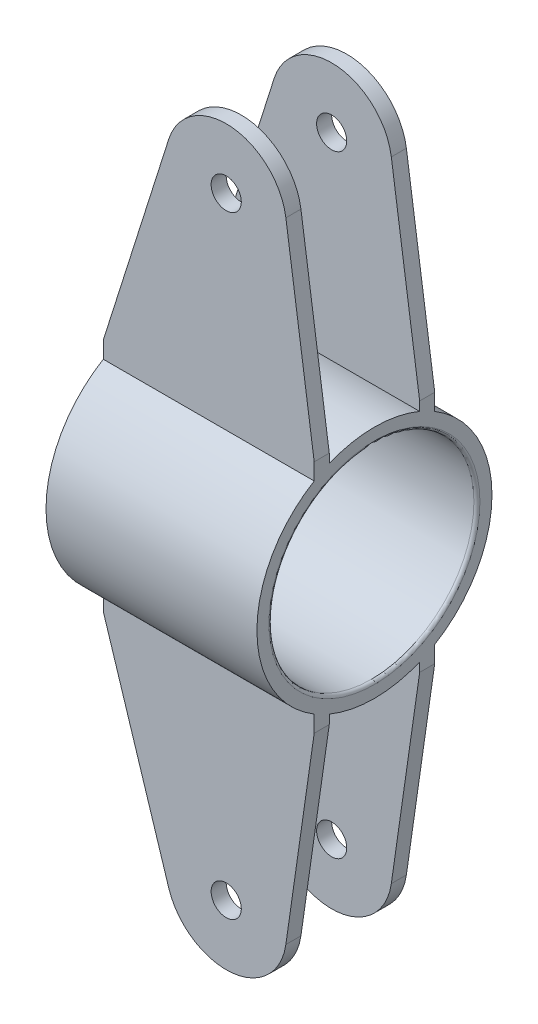
SolidWorks part; units mm, degrees
ref_plane "Front Plane" through (0, 0, 0) normal (0, 0, 1) x (1, 0, 0)
ref_plane "Top Plane" through (0, 0, 0) normal (0, 1, 0) x (1, 0, 0)
ref_plane "Right Plane" through (0, 0, 0) normal (1, 0, 0) x (0, 0, -1)
sketch "Sketch1" plane through (0, 0, 0) normal (1, 0, 0) x (0, 0, -1)
  circle A0 centre (0, 0) radius 34.007
  circle A1 centre (0, 0) radius 39.007
  dimension "D1" = 68.014
  dimension "D2" = 78.014
extrude "Boss-Extrude1" add sketch "Sketch1" along normal mid plane 70
sketch "Sketch2" plane through (0, 0, 0) normal (0, 0, 1) x (1, 0, 0)
  line L0 (-35, 0) -> (5.8, 0) construction
  line L1 (-35, 39.007) -> (-35, -39.007) construction
  line L2 (5.8, 101.6) -> (5.8, -101.6) construction
  line L3 (-35, -39.007) -> (35, -39.007) construction
  line L4 (35, 39.007) -> (-35, 39.007) construction
  line L5 (-35, -39.007) -> (35, -39.007)
  line L6 (35, 39.007) -> (-35, 39.007)
  line L7 (-35, 39.007) -> (-13.2668, 107.6378)
  line L8 (35, 39.007) -> (25.5966, 104.4448)
  line L9 (-35, -39.007) -> (-13.2668, -107.6378)
  line L10 (35, -39.007) -> (25.5966, -104.4448)
  circle A0 centre (5.8, 101.6) radius 5.007
  circle A1 centre (5.8, -101.6) radius 5.007
  arc A2 (25.5966, 104.4448) -> (-13.2668, 107.6378) centre (5.8, 101.6) ccw
  arc A3 (-13.2668, -107.6378) -> (25.5966, -104.4448) centre (5.8, -101.6) ccw
  point P8 (5.8, 0)
  dimension "D3" = 10.014
  dimension "D4" = 40
  dimension "D1" = 40.8
  dimension "D2" = 203.2
extrude "Boss-Extrude2" add sketch "Sketch2" along normal blind 5 from offset 15 separate body
sketch "Sketch3" plane through (0, 0, 0) normal (0, 0, 1) x (1, 0, 0)
  line L0 (-35, -39.007) -> (-13.2668, -107.6378) construction
  line L1 (25.5966, -104.4448) -> (35, -39.007) construction
  line L2 (35, -39.007) -> (-35, -39.007) construction
  line L3 (-35, 39.007) -> (35, 39.007) construction
  line L4 (-13.2668, 107.6378) -> (-35, 39.007) construction
  line L5 (35, 39.007) -> (25.5966, 104.4448) construction
  line L6 (-35, -39.007) -> (-13.2668, -107.6378)
  line L7 (25.5966, -104.4448) -> (35, -39.007)
  line L8 (35, -39.007) -> (-35, -39.007)
  line L9 (-35, 39.007) -> (35, 39.007)
  line L10 (-13.2668, 107.6378) -> (-35, 39.007)
  line L11 (35, 39.007) -> (25.5966, 104.4448)
  circle A0 centre (5.8, -101.6) radius 5.007 construction
  arc A1 (-13.2668, -107.6378) -> (25.5966, -104.4448) centre (5.8, -101.6) ccw construction
  circle A2 centre (5.8, 101.6) radius 5.007 construction
  arc A3 (25.5966, 104.4448) -> (-13.2668, 107.6378) centre (5.8, 101.6) ccw construction
  circle A4 centre (5.8, -101.6) radius 5.007
  arc A5 (-13.2668, -107.6378) -> (25.5966, -104.4448) centre (5.8, -101.6) ccw
  circle A6 centre (5.8, 101.6) radius 5.007
  arc A7 (25.5966, 104.4448) -> (-13.2668, 107.6378) centre (5.8, 101.6) ccw
extrude "Boss-Extrude3" add sketch "Sketch3" against normal blind 5 from offset 15 separate body offset against normal yes
sketch "Sketch4" plane through (35, 0, 0) normal (1, 0, 0) x (0, 0, -1)
  line L0 (20, -39.007) -> (15, -39.007) construction
  line L1 (-20, -39.007) -> (-15, -39.007) construction
  line L2 (-20, 39.007) -> (-15, 39.007) construction
  line L3 (20, 39.007) -> (15, 39.007) construction
  line L4 (20, -39.007) -> (15, -39.007)
  line L5 (-20, -39.007) -> (-15, -39.007)
  line L6 (-20, 39.007) -> (-15, 39.007)
  line L7 (20, 39.007) -> (15, 39.007)
  line L8 (-20, 39.007) -> (-20, 33.4895)
  line L9 (-15, 39.007) -> (-15, 36.0076)
  line L10 (15, 39.007) -> (15, 36.0076)
  line L11 (20, 39.007) -> (20, 33.4895)
  line L12 (-20, -39.007) -> (-20, -33.4895)
  line L13 (-15, -39.007) -> (-15, -36.0076)
  line L14 (15, -39.007) -> (15, -36.0076)
  line L15 (20, -39.007) -> (20, -33.4895)
  circle A0 centre (0, 0) radius 39.007 construction
  arc A1 (-20, -33.4895) -> (-15, -36.0076) centre (0, 0) ccw
  arc A2 (20, 33.4895) -> (15, 36.0076) centre (0, 0) ccw
  arc A3 (-15, 36.0076) -> (-20, 33.4895) centre (0, 0) ccw
  arc A4 (15, -36.0076) -> (20, -33.4895) centre (0, 0) ccw
extrude "Boss-Extrude4" add sketch "Sketch4" against normal up to surface (70 mm away) up to face at (-35, 0, -39.007)
ref_plane "Plane1" through (-25.9, 0, 0) normal (-1, 0, 0) x (0, 0, 1)
sketch "Sketch6" plane through (-25.9, 0, 0) normal (-1, 0, 0) x (0, 0, 1)
  line L0 (0, 0) -> (-39.007, 0) construction
  line L1 (0, 0) -> (0, 94.7171) construction
  line L2 (0, 0) -> (-56.4709, 50.6685) construction
  line L3 (-20, 33.4895) -> (-50.0988, 58.3754)
  line L4 (-39.007, 0) -> (-65.1511, 45.7031)
  arc A0 (-20, 33.4895) -> (-20, -33.4895) centre (0, 0) ccw construction
  arc A1 (-20, 33.4895) -> (-39.007, 0) centre (0, 0) ccw
  circle A2 centre (0, 0) radius 75.87 construction
  circle A3 centre (-56.4709, 50.6685) radius 3
  arc A4 (-50.0988, 58.3754) -> (-65.1511, 45.7031) centre (-56.4709, 50.6685) ccw
  dimension "D1" = 151.74
  dimension "D3" = 6
  dimension "D4" = 20
  dimension "D2" = 48.1
extrude "Boss-Extrude6" add sketch "Sketch6" against normal blind 4
fillet "Fillet1" radius 1 1 edges at (35, 0, -34.007)
fillet "Fillet2" radius 1 1 edges at (-35, 0, -34.007)
